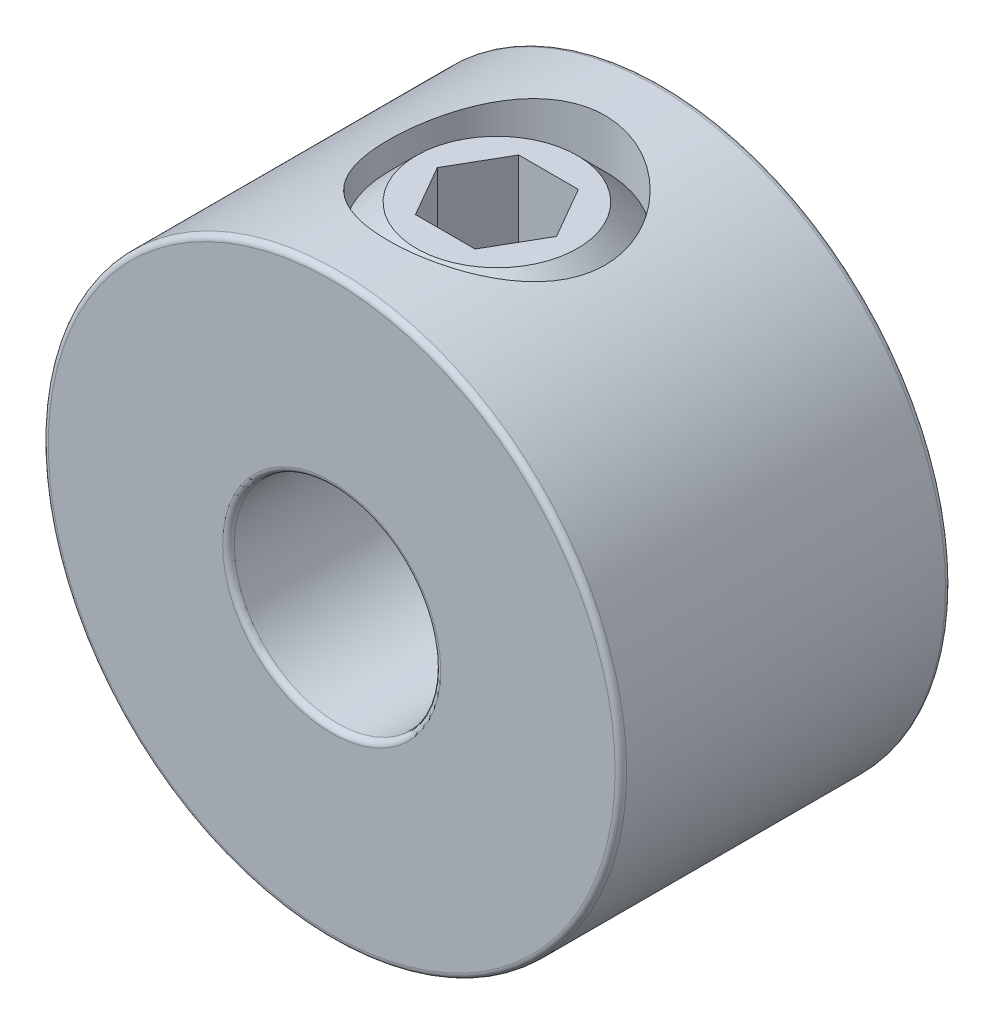
SolidWorks part; units mm, degrees
ref_plane "Front Plane" through (0, 0, 0) normal (0, 0, 1) x (1, 0, 0)
ref_plane "Top Plane" through (0, 0, 0) normal (0, 1, 0) x (1, 0, 0)
ref_plane "Right Plane" through (0, 0, 0) normal (1, 0, 0) x (0, 0, -1)
sketch "Sketch1" plane through (0, 0, 0) normal (0, 0, 1) x (1, 0, 0)
  circle A0 centre (0, 0) radius 5.5562
  circle A1 centre (0, 0) radius 1.9844
  point P4 (5.5562, 0)
  dimension "Bore Dia" = 3.9688
  dimension "OD" = 11.1125
extrude "Extrude1" add sketch "Sketch1" along normal mid plane 6.35
sketch "Sketch2" plane through (41.275, 0, 0) normal (0, -1, 0) x (0, 0, -1)
  line L0 (3.175, -41.275) -> (-3.175, -41.275) construction
  line L1 (-3.175, -35.7188) -> (-3.175, -46.8312) construction
  line L2 (3.175, -46.8312) -> (3.175, -35.7188) construction
  circle A0 centre (0, -41.275) radius 2.0828
  point P7 (0, -43.3578)
  dimension "Set Screw Dia" = 4.1656
extrude "Cut-Extrude1" cut sketch "Sketch2" against normal through all
fillet "Fillet1" radius 0.1111 4 edges at (1.9844, 0, -3.175) (1.9844, 0, 3.175) (5.5562, 0, -3.175) (5.5562, 0, 3.175)
sketch "Sketch3" plane through (0, 0, 0) normal (0, 0, 1) x (1, 0, 0)
  line L0 (-1.5473, 1.9844) -> (-0.6426, 1.9844)
  line L1 (0, 2.627) -> (-0.6426, 1.9844)
  line L2 (0, 2.627) -> (0, 5.1594)
  line L3 (0, 5.1594) -> (-1.5473, 5.1594)
  line L4 (-2.0828, 2.5199) -> (-2.0828, 4.6239)
  line L5 (0, 1.9844) -> (0, 0) construction
  line L6 (-2.0828, 2.5199) -> (-2.0828, 1.9844) construction
  line L7 (-2.0828, 1.9844) -> (-1.5473, 1.9844) construction
  line L8 (-2.0828, 4.6239) -> (-2.0828, 5.1594) construction
  line L9 (-1.5473, 1.9844) -> (-2.0828, 2.5199)
  line L10 (-2.0828, 4.6239) -> (-1.5473, 5.1594)
  line L11 (-2.0828, 5.1594) -> (-1.5473, 5.1594) construction
  line L12 (-0.6426, 1.9844) -> (0, 1.9844) construction
  line L13 (0, 1.9844) -> (0, 2.627) construction
  circle A1 centre (0, 0) radius 1.9844 construction
  dimension "Screw Length" = 3.175
  dimension "D2" = 0.5355
  dimension "D1" = 0.6426
revolve "Revolve1" add sketch "Sketch3" angle 360 about L5
sketch "Sketch4" plane through (3.3734, 5.1594, 0) normal (0, -1, 0) x (0, 0, -1)
  line L1 (0, -2.2278) -> (-0.9922, -2.8006)
  line L2 (-0.9922, -2.8006) -> (-0.9922, -3.9463)
  line L3 (-0.9922, -3.9463) -> (0, -4.5191)
  line L4 (0, -4.5191) -> (0.9922, -3.9463)
  line L5 (0.9922, -3.9463) -> (0.9922, -2.8006)
  line L6 (0.9922, -2.8006) -> (0, -2.2278)
  circle A0 centre (0, -3.3734) radius 0.9922 construction
  circle A1 centre (0, -3.3734) radius 1.1457 construction
  dimension "D1" = 2.2914
  dimension "Hex Size" = 1.9844
extrude "Cut-Extrude2" cut sketch "Sketch4" along normal blind 1.9844
equation "\"D1@Fillet1\" = \"OD@Sketch1\"*.01"
equation "\"D1@Cut-Extrude2\" = \"Hex Size@Sketch4\""
equation "\"D2@Sketch3\" =(\"Set Screw Dia@Sketch2\"-\"D1@Sketch4\")/3.5"
equation "\"D1@Sketch3\" = \"D2@Sketch3\"*1.2"
